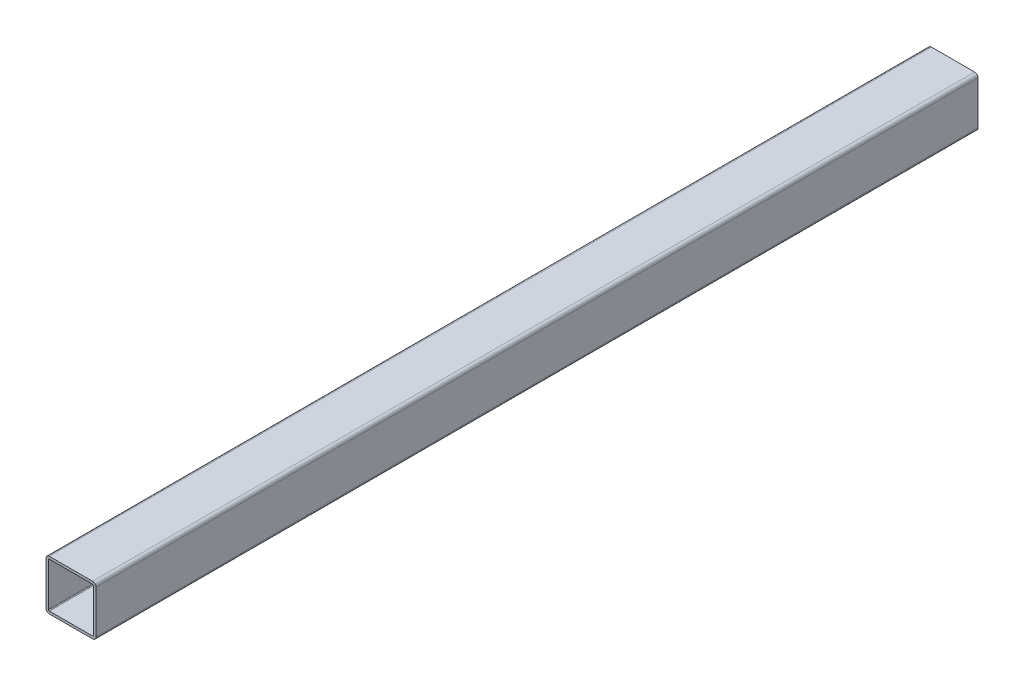
SolidWorks part; units mm, degrees
ref_plane "Спереди" through (0, 0, 0) normal (0, 0, 1) x (1, 0, 0)
ref_plane "Сверху" through (0, 0, 0) normal (0, 1, 0) x (1, 0, 0)
ref_plane "Справа" through (0, 0, 0) normal (1, 0, 0) x (0, 0, -1)
sketch "Эскиз1" plane through (0, 0, 0) normal (0, 0, 1) x (1, 0, 0)
  line L1 (2, 0) -> (28, 0)
  line L2 (0, 2) -> (0, 28)
  line L3 (2, 30) -> (28, 30)
  line L4 (30, 2) -> (30, 28)
  arc A0 (0, 2) -> (2, 0) centre (2, 2) ccw
  arc A1 (30, 2) -> (28, 0) centre (28, 2) cw
  arc A2 (28, 30) -> (30, 28) centre (28, 28) cw
  arc A3 (2, 30) -> (0, 28) centre (2, 28) ccw
  point P7 (0, 0)
  dimension "D3" = 2
  dimension "D1" = 30
  dimension "D2" = 30
extrude "Вытянуть-Тонкостенный1" add sketch "Эскиз1" along normal blind 530 thin thin type one direction reverse wall 1.5
